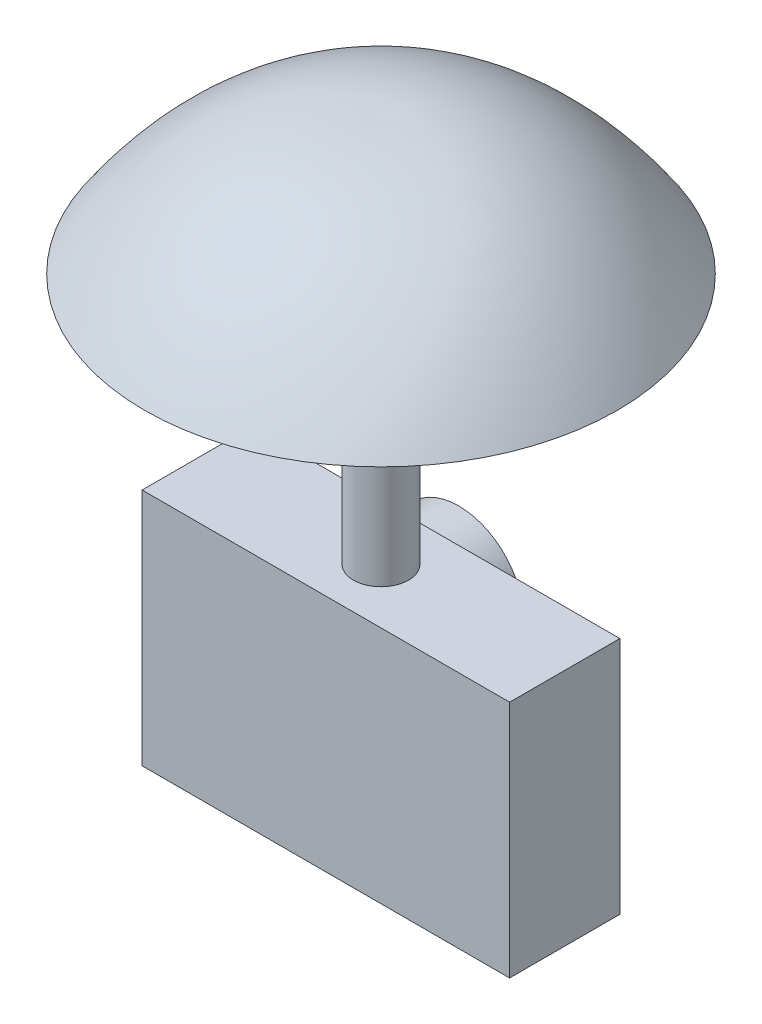
SolidWorks part; units mm, degrees
ref_plane "Front Plane" through (0, 0, 0) normal (0, 0, 1) x (1, 0, 0)
ref_plane "Top Plane" through (0, 0, 0) normal (0, 1, 0) x (1, 0, 0)
ref_plane "Right Plane" through (0, 0, 0) normal (1, 0, 0) x (0, 0, -1)
sketch "Sketch1" plane through (0, 0, 0) normal (0, 1, 0) x (1, 0, 0)
  line L1 (0, 0) -> (20, 0)
  line L2 (0, 0) -> (0, 6)
  line L3 (0, 6) -> (20, 6)
  line L4 (20, 0) -> (20, 6)
  dimension "D1" = 6
  dimension "D2" = 20
extrude "Boss-Extrude1" add sketch "Sketch1" along normal blind 13
sketch "Sketch2" plane through (0, 0, 0) normal (0, -1, 0) x (1, 0, 0)
  line L0 (0, 0) -> (20, 0) construction
  line L1 (0, -6) -> (0, 0) construction
  circle A0 centre (10, -3) radius 1.5
  dimension "D2" = 10
  dimension "D3" = 3
  dimension "D1" = 3
extrude "Boss-Extrude3" add sketch "Sketch2" against normal blind 34
ref_plane "Plane1" through (0, 0, -3) normal (0, 0, 1) x (1, 0, 0)
sketch "Sketch5" plane through (0, 0, -3) normal (0, 0, 1) x (1, 0, 0)
  line L0 (10, 34) -> (10, 26.6872)
  line L1 (11.5, 34) -> (8.5, 34) construction
  line L2 (10, 26.6872) -> (-2.866, 26.6872)
  spline S0 degree 2 poles (10, 34) (2.3731, 34.4058) (-2.866, 26.6872) knots 0 0 0 1 1 1
revolve "Revolve1" add sketch "Sketch5" angle 360 about L0
sketch "Sketch6" plane through (0, 0, -6) normal (0, 0, -1) x (-1, 0, 0)
  circle A0 centre (-6.2355, 6.36) radius 3.5055
extrude "Boss-Extrude4" add sketch "Sketch6" along normal blind 5
